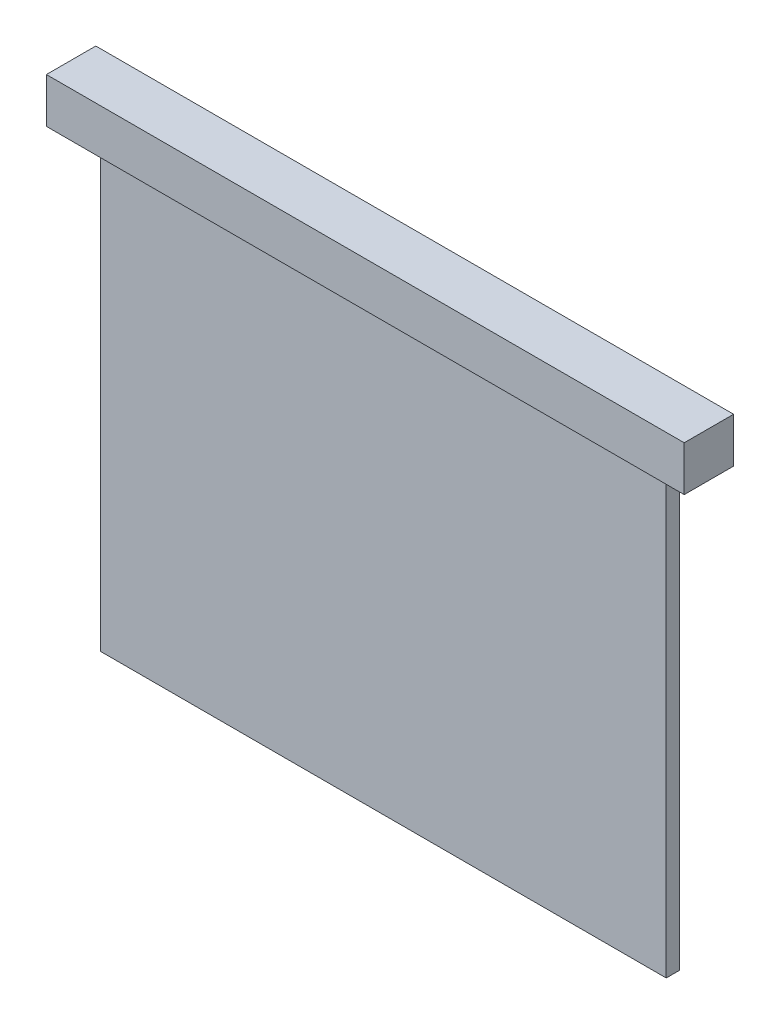
SolidWorks part; units mm, degrees
ref_plane "Front Plane" through (0, 0, 0) normal (0, 0, 1) x (1, 0, 0)
ref_plane "Top Plane" through (0, 0, 0) normal (0, 1, 0) x (1, 0, 0)
ref_plane "Right Plane" through (0, 0, 0) normal (1, 0, 0) x (0, 0, -1)
sketch "Sketch3" plane through (0, 0, 0) normal (0, 0, 1) x (1, 0, 0)
  line L1 (-31.5, -24.8) -> (31.5, -24.8)
  line L2 (-31.5, -24.8) -> (-31.5, 24.8)
  line L3 (-31.5, 24.8) -> (31.5, 24.8)
  line L4 (31.5, -24.8) -> (31.5, 24.8)
  line L5 (-31.5, -24.8) -> (31.5, 24.8) construction
  line L6 (-31.5, 24.8) -> (31.5, -24.8) construction
  point P0 (0, 0)
extrude "Boss-Extrude1" add sketch "Sketch3" along normal blind 1.5
sketch "Sketch10" plane through (31.5, 0, 0) normal (1, 0, 0) x (0, 0, -1)
  line L0 (-1.5, 24.8) -> (0, 24.8)
  line L1 (-1.5, 24.8) -> (-1.5, 29.8)
  line L2 (0, 24.8) -> (0, 29.8)
  line L3 (-1.5, 29.8) -> (0, 29.8)
  line L4 (-1.5, 29.8) -> (-1.5, 24.8)
  line L5 (-1.5, 29.8) -> (-3.5, 29.8)
  line L6 (-1.5, 24.8) -> (-3.5, 24.8)
  line L7 (-3.5, 29.8) -> (-3.5, 24.8)
  line L8 (0, 29.8) -> (0, 24.8)
  line L9 (0, 29.8) -> (2, 29.8)
  line L10 (0, 24.8) -> (2, 24.8)
  line L11 (2, 29.8) -> (2, 24.8)
  line M14 (0, 24.8) -> (-1.5, 24.8)
extrude "Boss-Extrude2" add sketch "Sketch10" against normal blind 63 contours L5 L7 L6 L1 | L3 L1 L2 M14 | L11 L9 L2 L10
sketch "Sketch11" plane through (31.5, 0, 0) normal (1, 0, 0) x (0, 0, -1)
  line L0 (-3.5, 29.8) -> (2, 29.8)
  line L1 (-3.5, 29.8) -> (-3.5, 24.7973)
  line L2 (2, 29.8) -> (2, 24.7973)
  line L3 (-3.5, 24.7973) -> (2, 24.7973)
extrude "Boss-Extrude3" add sketch "Sketch11" along normal blind 4
sketch "Sketch12" plane through (-31.5, 0, 0) normal (-1, 0, 0) x (0, 0, 1)
  line L0 (-2, 29.8) -> (3.5, 29.8)
  line L1 (-2, 29.8) -> (-2, 24.8)
  line L2 (3.5, 29.8) -> (3.5, 24.8)
  line L3 (-2, 24.8) -> (3.5, 24.8)
extrude "Boss-Extrude4" add sketch "Sketch12" along normal blind 4
